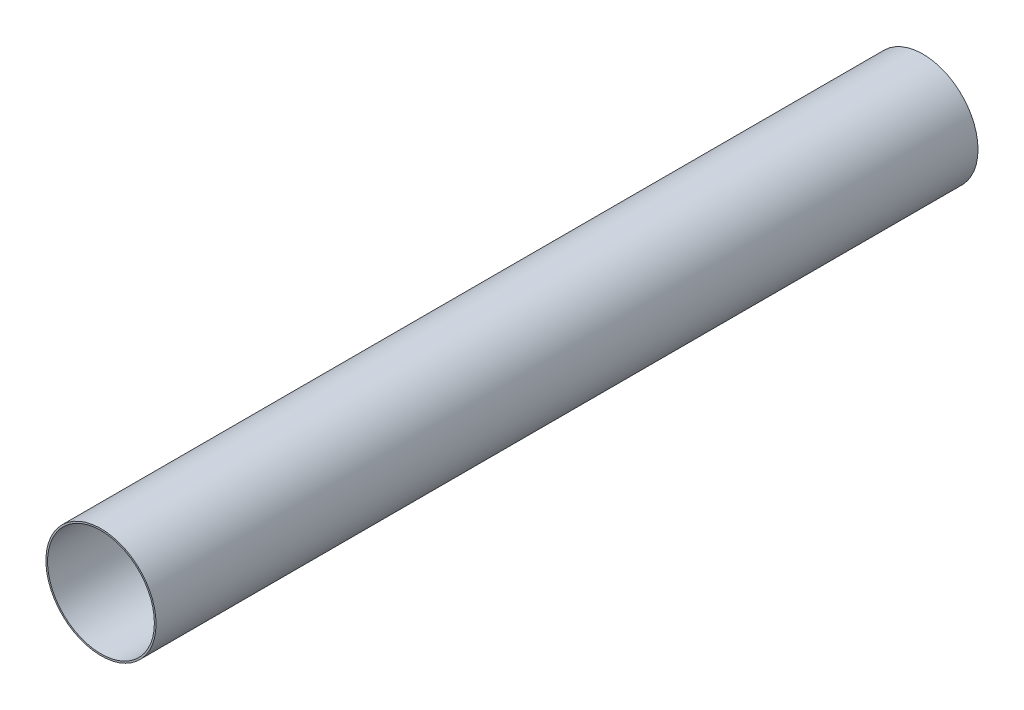
SolidWorks part; units mm, degrees
ref_plane "Front Plane" through (0, 0, 0) normal (0, 0, 1) x (1, 0, 0)
ref_plane "Top Plane" through (0, 0, 0) normal (0, 1, 0) x (1, 0, 0)
ref_plane "Right Plane" through (0, 0, 0) normal (1, 0, 0) x (0, 0, -1)
sketch "Sketch1" plane through (0, 0, 0) normal (0, 0, 1) x (1, 0, 0)
  circle A0 centre (0, 0) radius 49.53
  circle A1 centre (0, 0) radius 51.054
  dimension "D1" = 102.108
  dimension "D2" = 99.06
extrude "Boss-Extrude1" add sketch "Sketch1" along normal blind 762
